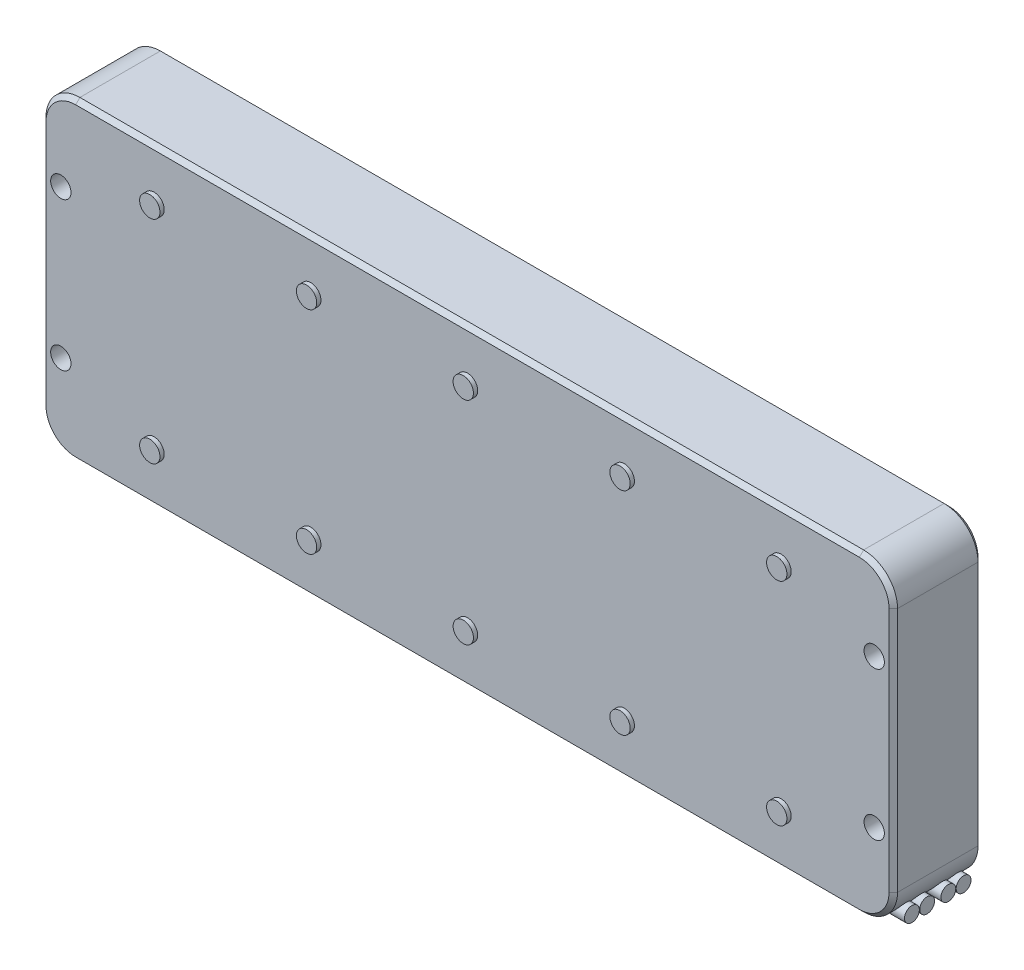
SolidWorks part; units mm, degrees
ref_plane "Front" through (0, 0, 0) normal (0, 0, 1) x (1, 0, 0)
ref_plane "Top" through (0, 0, 0) normal (0, 1, 0) x (1, 0, 0)
ref_plane "Right" through (0, 0, 0) normal (1, 0, 0) x (0, 0, -1)
sketch "Sketch1" plane through (0, 0, 0) normal (0, 0, 1) x (1, 0, 0)
  line L1 (-100.5, -37) -> (100.5, -37)
  line L2 (-100.5, -37) -> (-100.5, 37)
  line L3 (-100.5, 37) -> (100.5, 37)
  line L4 (100.5, -37) -> (100.5, 37)
  line L5 (-100.5, -37) -> (100.5, 37) construction
  line L6 (-100.5, 37) -> (100.5, -37) construction
  point P0 (0, 0)
  dimension "D1" = 201
  dimension "D2" = 74
extrude "Boss-Extrude1" add sketch "Sketch1" along normal blind 21
fillet "Fillet1" radius 8 4 edges at (100.5, 37, 10.5) (100.5, -37, 10.5) (-100.5, -37, 10.5) (-100.5, 37, 10.5)
chamfer "Chamfer1" distance 1 angle 45 16 edges at (0, 37, 0) (-98.1569, 34.6569, 0) (98.1569, 34.6569, 0) (-100.5, 0, 0) (100.5, 0, 0) (-98.1569, -34.6569, 0) (98.1569, -34.6569, 0) (0, -37, 0) (0, 37, 21) (-98.1569, 34.6569, 21) (98.1569, 34.6569, 21) (-100.5, 0, 21) (100.5, 0, 21) (-98.1569, -34.6569, 21) (98.1569, -34.6569, 21) (0, -37, 21)
sketch "Sketch2" plane through (0, 0, 21) normal (0, 0, 1) x (1, 0, 0)
  line L0 (-100.5, 0) -> (100.5, 0) construction
  line L1 (-100.5, -29) -> (-100.5, 29) construction
  line L2 (100.5, 29) -> (100.5, -29) construction
  line L3 (0, 37) -> (0, -37) construction
  line L4 (-92.5, 37) -> (92.5, 37) construction
  line L5 (92.5, -37) -> (-92.5, -37) construction
  line L6 (-96, 17.5) -> (-96, -17.5) construction
  circle A0 centre (-96, 17.5) radius 2.4
  circle A1 centre (-96, -17.5) radius 2.4
  circle A2 centre (96, 17.5) radius 2.4
  circle A3 centre (96, -17.5) radius 2.4
  point P16 (-96, 0)
  dimension "D1" = 4.8
  dimension "D2" = 35
  dimension "D3" = 4.5
extrude "Cut-Extrude1" cut sketch "Sketch2" against normal up to next
sketch "Sketch3" plane through (0, 0, 21) normal (0, 0, 1) x (1, 0, 0)
  line L0 (-100.5, 0) -> (100.5, 0) construction
  line L1 (-100.5, -29) -> (-100.5, 29) construction
  line L2 (100.5, 29) -> (100.5, -29) construction
  line L3 (0, 25) -> (0, 0) construction
  line L6 (-74, 25) -> (-37, 25) construction
  line L7 (-37, 25) -> (0, 25) construction
  line L8 (0, 0) -> (0, -25) construction
  line L9 (0, 25) -> (37, 25) construction
  line L10 (37, 25) -> (74, 25) construction
  line L11 (74, -25) -> (37, -25) construction
  line L12 (37, -25) -> (0, -25) construction
  line L13 (0, -25) -> (-37, -25) construction
  line L14 (-37, -25) -> (-74, -25) construction
  line L15 (-74, 25) -> (-74, -25) construction
  line L16 (-37, -25) -> (-37, 25) construction
  line L17 (37, 25) -> (37, -25) construction
  line L18 (74, 25) -> (74, -25) construction
  line L19 (-92.5, 37) -> (92.5, 37) construction
  circle A0 centre (0, 25) radius 2.4
  circle A1 centre (0, -25) radius 2.4
  circle A2 centre (-74, 25) radius 2.4
  circle A3 centre (-37, 25) radius 2.4
  circle A4 centre (37, 25) radius 2.4
  circle A5 centre (74, 25) radius 2.4
  circle A6 centre (74, -25) radius 2.4
  circle A7 centre (37, -25) radius 2.4
  circle A8 centre (-37, -25) radius 2.4
  circle A9 centre (-74, -25) radius 2.4
  dimension "D1" = 4.8
  dimension "D2" = 37
  dimension "D3" = 12
extrude "Boss-Extrude2" add sketch "Sketch3" along normal blind 1
sketch "Sketch4" plane through (100.5, 0, 0) normal (1, 0, 0) x (0, 0, -1)
  line L0 (-16.6, -35.15) -> (-13, -35.15) construction
  line L1 (-8, -35.15) -> (-4.4, -35.15) construction
  line L2 (-10.5, 37) -> (-10.5, -37) construction
  line L3 (-20, 37) -> (-1, 37) construction
  line L4 (-1, -37) -> (-20, -37) construction
  line L5 (-13, -35.15) -> (-8, -35.15) construction
  line L6 (-16.6, -36.9) -> (-4.4, -36.9) construction
  circle A0 centre (-16.6, -35.15) radius 1.75
  circle A1 centre (-13, -35.15) radius 1.75
  circle A2 centre (-8, -35.15) radius 1.75
  circle A3 centre (-4.4, -35.15) radius 1.75
  point P14 (-10.5, -35.15)
  dimension "D1" = 3.5
  dimension "D2" = 5
  dimension "D3" = 0.1
  dimension "D4" = 3.6
extrude "Boss-Extrude6" add sketch "Sketch4" against normal up to next
sketch "Sketch5" plane through (0, 0, 0) normal (0, 0, -1) x (-1, 0, 0)
  line L0 (-135.4312, 0) -> (100.5, 0) construction
  line L1 (0, 25) -> (0, 0) construction
  line L2 (-74, 25) -> (-37, 25) construction
  line L3 (-37, 25) -> (0, 25) construction
  line L4 (0, 0) -> (0, -25) construction
  line L5 (0, 25) -> (37, 25) construction
  line L6 (37, 25) -> (74, 25) construction
  line L7 (74, -25) -> (37, -25) construction
  line L8 (37, -25) -> (0, -25) construction
  line L9 (0, -25) -> (-37, -25) construction
  line L10 (-37, -25) -> (-74, -25) construction
  line L11 (-74, 25) -> (-74, -25) construction
  line L12 (-37, -25) -> (-37, 25) construction
  line L13 (37, 25) -> (37, -25) construction
  line L14 (74, 25) -> (74, -25) construction
  line L15 (100.5, 29) -> (100.5, -29) construction
  line L16 (-92.5, 37) -> (92.5, 37) construction
  circle A0 centre (0, 25) radius 2.4
  circle A1 centre (0, -25) radius 2.4
  circle A2 centre (-74, 25) radius 2.4
  circle A3 centre (-37, 25) radius 2.4
  circle A4 centre (37, 25) radius 2.4
  circle A5 centre (74, 25) radius 2.4
  circle A6 centre (74, -25) radius 2.4
  circle A7 centre (37, -25) radius 2.4
  circle A8 centre (-37, -25) radius 2.4
  circle A9 centre (-74, -25) radius 2.4
  point P27 (100.5, 0)
  dimension "D1" = 4.8
  dimension "D2" = 37
  dimension "D3" = 12
extrude "Cut-Extrude2" cut sketch "Sketch5" against normal blind 1
sketch "Sketch6" plane through (0, -37, 0) normal (0, -1, 0) x (1, 0, 0)
  line L0 (-100.5, 1) -> (-100.5, 20) construction
  line L5 (-92.5, 21) -> (92.5, 21) construction
  line L7 (-69.5, 15) -> (-56.5, 15)
  line L8 (-69.5, 15) -> (-69.5, 6)
  line L9 (-69.5, 6) -> (-56.5, 6)
  line L10 (-56.5, 15) -> (-56.5, 6)
  line L11 (-69.5, 15) -> (-56.5, 6) construction
  line L12 (-69.5, 6) -> (-56.5, 15) construction
  circle A0 centre (-63, 10.5) radius 2 construction
  dimension "D1" = 4
  dimension "D2" = 37.5
  dimension "D3" = 10.5
  dimension "D4" = 13
  dimension "D5" = 9
extrude "Cut-Extrude3" cut sketch "Sketch6" against normal blind 2.4
sketch "Sketch7" plane through (0, -34.6, 0) normal (0, -1, 0) x (1, 0, 0)
  line L0 (-69.5, 15) -> (-56.5, 6) construction
  line L2 (-69.5, 6) -> (-56.5, 15) construction
  circle A0 centre (-63, 10.5) radius 2
  dimension "D1" = 4
extrude "Boss-Extrude7" add sketch "Sketch7" along normal blind 1.25
fillet "Fillet2" radius 2.5 4 edges at (-56.5, -35.8, 6) (-69.5, -35.8, 6) (-56.5, -35.8, 15) (-69.5, -35.8, 15)
sketch "Sketch8" plane through (0, -37, 0) normal (0, -1, 0) x (1, 0, 0)
  line L0 (100.5, 1) -> (100.5, 20) construction
  line L1 (-92.5, 0) -> (92.5, 0) construction
  circle A0 centre (55.5, 6) radius 2.5
  dimension "D1" = 5
  dimension "D2" = 45
  dimension "D3" = 6
extrude "Cut-Extrude4" cut sketch "Sketch8" against normal blind 0.25
pattern_linear "LPattern1" count 5 spacing 25 along (-1, 0, 0) of "Cut-Extrude4"
